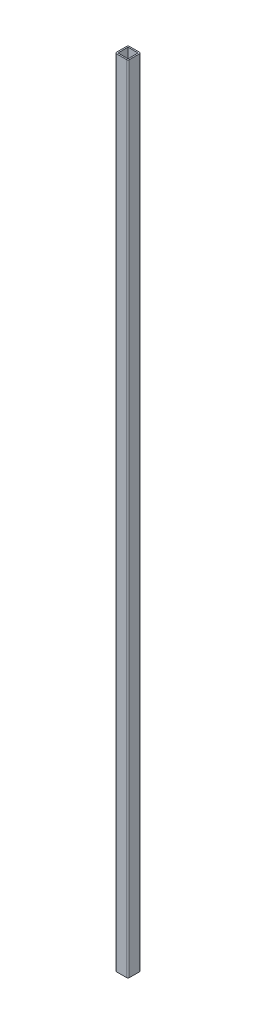
SolidWorks part; units mm, degrees
material "Plain Carbon Steel"
ref_plane "Front Plane" through (0, 0, 0) normal (0, 0, 1) x (1, 0, 0)
ref_plane "Top Plane" through (0, 0, 0) normal (0, 1, 0) x (1, 0, 0)
ref_plane "Right Plane" through (0, 0, 0) normal (1, 0, 0) x (0, 0, -1)
sketch "Sketch1" plane through (0, 0, 0) normal (0, 1, 0) x (1, 0, 0)
  line L1 (2.8, 0) -> (22.8, 0)
  line L2 (0, -2.8) -> (0, -22.8)
  line L3 (2.8, -25.6) -> (22.8, -25.6)
  line L4 (25.6, -2.8) -> (25.6, -22.8)
  arc A0 (22.8, 0) -> (25.6, -2.8) centre (22.8, -2.8) cw
  arc A1 (22.8, -25.6) -> (25.6, -22.8) centre (22.8, -22.8) ccw
  arc A2 (0, -22.8) -> (2.8, -25.6) centre (2.8, -22.8) ccw
  arc A3 (2.8, 0) -> (0, -2.8) centre (2.8, -2.8) ccw
  point P7 (25.6, 0)
  point P10 (25.6, -25.6)
  point P15 (0, 0)
  dimension "D2" = 2.8
  dimension "D1" = 25.6
extrude "Boss-Extrude1" add sketch "Sketch1" along normal blind 1580
sketch "Sketch3" plane through (0, 0, 0) normal (0, -1, 0) x (-1, 0, 0)
  line L4 (-2.8, -2.8) -> (-22.8, -2.8)
  line L5 (-2.8, -2.8) -> (-2.8, -22.8)
  line L6 (-2.8, -22.8) -> (-22.8, -22.8)
  line L7 (-22.8, -2.8) -> (-22.8, -22.8)
  line L8 (-2.8, -2.8) -> (-22.8, -22.8) construction
  line L9 (-2.8, -22.8) -> (-22.8, -2.8) construction
  point P6 (-12.8, -12.8)
extrude "Cut-Extrude1" cut sketch "Sketch3" against normal blind 1770
